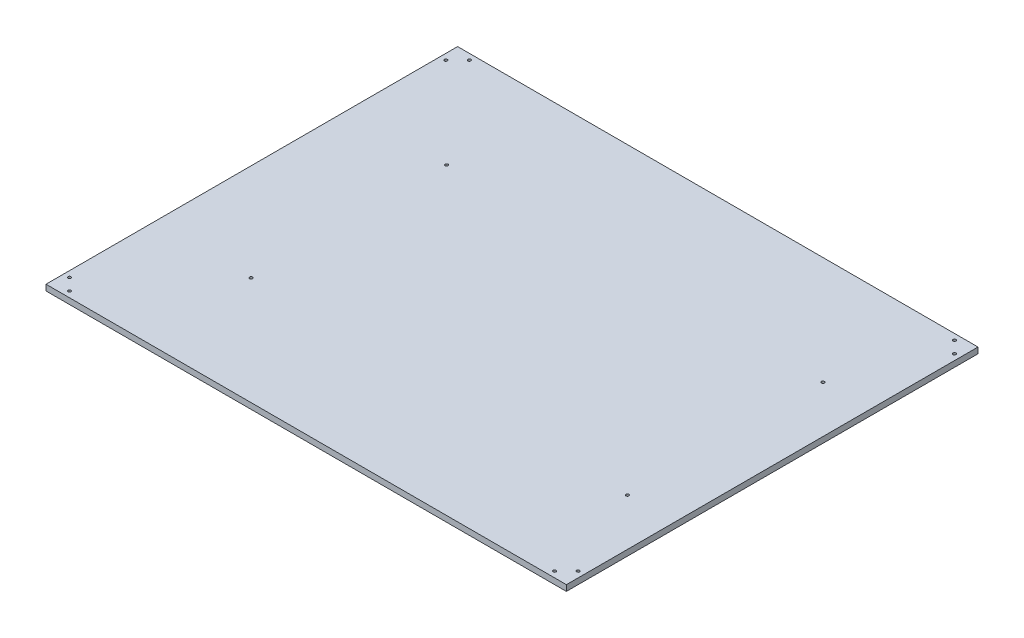
SolidWorks part; units mm, degrees
ref_plane "Front Plane" through (0, 0, 0) normal (0, 0, 1) x (1, 0, 0)
ref_plane "Top Plane" through (0, 0, 0) normal (0, 1, 0) x (1, 0, 0)
ref_plane "Right Plane" through (0, 0, 0) normal (1, 0, 0) x (0, 0, -1)
sketch "Sketch1" plane through (0, 0, 0) normal (0, 1, 0) x (1, 0, 0)
  line L1 (0, 0) -> (885, 0)
  line L2 (0, 0) -> (0, 700)
  line L3 (0, 700) -> (885, 700)
  line L4 (885, 0) -> (885, 700)
  dimension "D1" = 885
  dimension "D2" = 700
extrude "Boss-Extrude1" add sketch "Sketch1" along normal blind 10
sketch "Sketch2" plane through (0, 10, 0) normal (0, 1, 0) x (1, 0, 0)
  line L0 (885, 0) -> (885, 700) construction
  line L1 (805, 183.75) -> (805, 516.25)
  line L2 (0, 0) -> (885, 0) construction
  circle A0 centre (805, 183.75) radius 2.5
  circle A1 centre (805, 516.25) radius 2.5
  circle A2 centre (165, 183.75) radius 2.5
  circle A3 centre (165, 516.25) radius 2.5
  point P6 (805, 350)
  dimension "D2" = 5
  dimension "D5" = 5
  dimension "D1" = 80
  dimension "D3" = 332.5
  dimension "D4" = 80
  dimension "D6" = 350
  dimension "D7" = 2
extrude "Cut-Extrude1" cut sketch "Sketch2" against normal blind 10
sketch "Sketch3" plane through (0, 10, 0) normal (0, 1, 0) x (1, 0, 0)
  line L0 (0, 0) -> (885, 0) construction
  line L1 (0, 700) -> (0, 0) construction
  line L2 (885, 700) -> (0, 700) construction
  line L3 (885, 0) -> (885, 700) construction
  circle A0 centre (875, 10) radius 2.5
  circle A1 centre (875, 690) radius 2.5
  circle A2 centre (10, 690) radius 2.5
  circle A3 centre (10, 10) radius 2.5
  dimension "D3" = 5
  dimension "D6" = 5
  dimension "D7" = 10
  dimension "D8" = 10
  dimension "D9" = 5
  dimension "D12" = 5
  dimension "D1" = 10
  dimension "D2" = 10
  dimension "D4" = 10
  dimension "D5" = 10
  dimension "D10" = 10
  dimension "D11" = 10
sketch "Sketch4" plane through (0, 10, 0) normal (0, 1, 0) x (1, 0, 0)
  line L0 (885, 0) -> (885, 700) construction
  line L1 (885, 700) -> (0, 700) construction
  circle A0 centre (875, 670) radius 2.5
  circle A1 centre (855, 690) radius 2.5
  dimension "D4" = 5
  dimension "D5" = 5
  dimension "D1" = 30
  dimension "D2" = 30
  dimension "D3" = 10
  dimension "D6" = 10
extrude "Cut-Extrude2" cut sketch "Sketch4" against normal blind 10
ref_plane "Plane1" through (0, 0, -350) normal (0, 0, 1) x (1, 0, 0)
mirror "Mirror1" about plane through (0, 0, -350) normal (0, 0, 1) of "Cut-Extrude2"
ref_plane "Plane2" through (442.5, 0, 0) normal (-1, 0, 0) x (0, 0, 1)
mirror "Mirror2" about plane through (442.5, 0, 0) normal (-1, 0, 0) of "Cut-Extrude2", "Mirror1"
